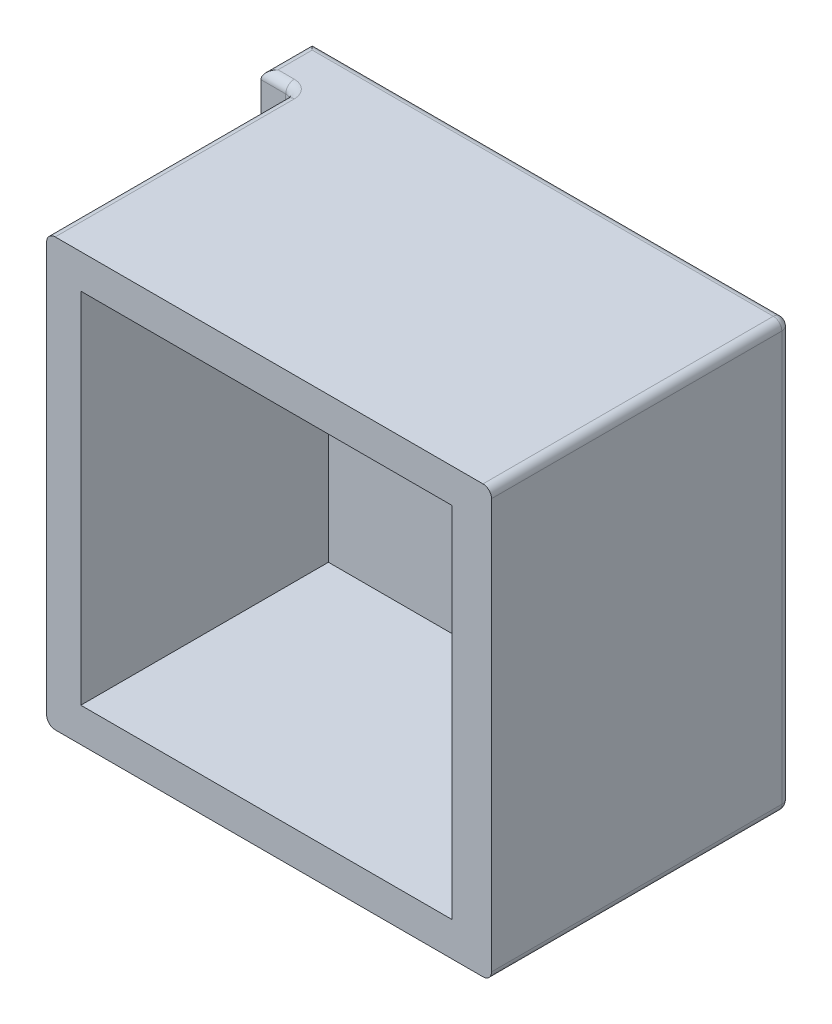
SolidWorks part; units mm, degrees
ref_plane "Plano frontal" through (0, 0, 0) normal (0, 0, 1) x (1, 0, 0)
ref_plane "Plano superior" through (0, 0, 0) normal (0, 1, 0) x (1, 0, 0)
ref_plane "Plano direito" through (0, 0, 0) normal (1, 0, 0) x (0, 0, -1)
sketch "Esboço1" plane through (0, 0, 0) normal (0, 0, 1) x (1, 0, 0)
  line L0 (5.4916, 13.9031) -> (5.4916, -36.0969) construction
  line L1 (-23.7184, 13.9031) -> (32.2816, 13.9031)
  line L2 (-23.7184, 13.9031) -> (-23.7184, -36.0969)
  line L3 (-23.7184, -36.0969) -> (32.2816, -36.0969)
  line L4 (32.2816, 13.9031) -> (32.2816, -36.0969)
  line L5 (-23.7184, -11.0969) -> (32.2816, -11.0969) construction
  circle A0 centre (5.4916, -11.0969) radius 5
  dimension "D1" = 56
  dimension "D2" = 50
  dimension "D3" = 29.21
extrude "Ressalto-extrusão1" add sketch "Esboço1" along normal blind 6
sketch "Esboço2" plane through (0, 0, 6) normal (0, 0, 1) x (1, 0, 0)
  line L0 (4.2816, 13.9031) -> (4.2816, -36.0969) construction
  line L1 (32.2816, 13.9031) -> (-23.7184, 13.9031) construction
  line L2 (-23.7184, -36.0969) -> (32.2816, -36.0969) construction
  line L3 (32.2816, -36.0969) -> (32.2816, 13.9031) construction
  line L4 (-15.8184, 9.9031) -> (27.6816, 9.9031)
  line L5 (-15.8184, 9.9031) -> (-15.8184, -32.0969)
  line L6 (-15.8184, -32.0969) -> (27.6816, -32.0969)
  line L7 (27.6816, 9.9031) -> (27.6816, -32.0969)
  line L9 (-19.8184, 13.9031) -> (-19.8184, -36.0969)
  line L10 (-19.8184, 13.9031) -> (32.2816, 13.9031)
  line L11 (32.2816, 13.9031) -> (32.2816, -36.0969)
  line L12 (32.2816, -36.0969) -> (-19.8184, -36.0969)
  dimension "D1" = 4
  dimension "D2" = 4.6
  dimension "D3" = 43.5
  dimension "D4" = 4
  dimension "D5" = 4
extrude "Ressalto-extrusão2" add sketch "Esboço2" along normal blind 29
fillet "Filete1" radius 1 12 edges at (-21.7684, 13.9031, 6) (-21.7684, -36.0969, 6) (4.2816, -36.0969, 0) (4.2816, 13.9031, 0) (32.2816, -11.0969, 0) (-23.7184, -36.0969, 3) (-23.7184, 13.9031, 3) (-19.8184, -11.0969, 6) (-19.8184, 13.9031, 20.5) (-19.8184, -36.0969, 20.5) (32.2816, -36.0969, 17.5) (32.2816, 13.9031, 17.5)
